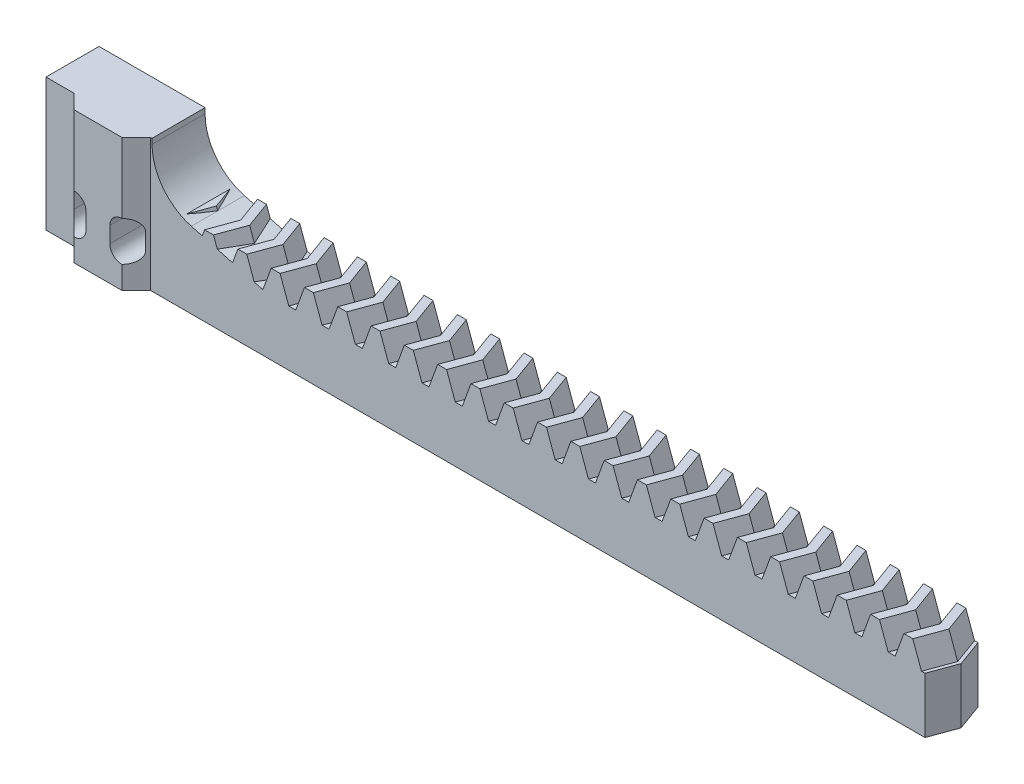
SolidWorks part; units mm, degrees
material "3D printed plastic"
ref_plane "Front Plane" through (0, 0, 0) normal (0, 0, 1) x (1, 0, 0)
ref_plane "Top Plane" through (0, 0, 0) normal (0, 1, 0) x (1, 0, 0)
ref_plane "Right Plane" through (0, 0, 0) normal (1, 0, 0) x (0, 0, -1)
sketch "Sketch1" plane through (0, 0, 0) normal (0, 0, 1) x (1, 0, 0)
  line L21 (-3.14, -10.5) -> (3.14, -10.5)
  line L22 (3.14, -10.5) -> (3.14, 0)
  line L23 (3.14, 0) -> (2.4799, 0)
  line L24 (2.4799, 0) -> (0.8421, 4.5)
  line L25 (0.8421, 4.5) -> (-0.8421, 4.5)
  line L26 (-0.8421, 4.5) -> (-2.4799, 0)
  line L27 (-2.4799, 0) -> (-3.14, 0)
  line L28 (-3.14, 0) -> (-3.14, -10.5)
  line L29 (0, -10.5) -> (0, 4.5) construction
  line L30 (-2.4799, 0) -> (2.4799, 0) construction
  line L31 (-1.57, 2.5) -> (-3.14, 2.5) construction
  line L32 (-1.57, 2.5) -> (0, 2.5) construction
  line L33 (0, 2.5) -> (1.57, 2.5) construction
  line L34 (1.57, 2.5) -> (3.14, 2.5) construction
  line L35 (3.14, 2.5) -> (3.14, 0) construction
  line L36 (-3.14, 2.5) -> (-3.14, 0) construction
  line L37 (-3.14, 0) -> (-3.126, -0.0106) construction
  dimension "D7" = 20
  dimension "D8" = 4.5
  dimension "D9" = 6.28
  dimension "D10" = 2
  dimension "D11" = 10.5
sketch "Sketch2" plane through (0, 0, 0) normal (0, 1, 0) x (1, 0, 0)
  line L0 (0, 0) -> (-1.8199, 5)
  line L1 (-2.4799, 0) -> (2.4799, 0) construction
  dimension "D1" = 70
  dimension "D2" = 5
sweep "Sweep1" add profiles "Sketch1" path "Sketch2"
mirror "Mirror2" about plane through (0, 0, 0) normal (0, 0, 1) of "Sweep1"
pattern_linear "LPattern2" count 24 spacing 6.28 along (1, 0, 0) of "Mirror2", "Sweep1"
sketch "Sketch3" plane through (0, 0, 5) normal (0, 0, 1) x (1, 0, 0)
  line L0 (0, 13.5) -> (0, 14.5)
  line L1 (0, -10.5) -> (-20, -10.5)
  line L2 (-4.9599, -10.5) -> (145.7601, -10.5) construction
  line L3 (0, -10.5) -> (0, 0) construction
  line L4 (21.7457, 0) -> (21.7457, -10.5)
  line L5 (0, 14.5) -> (-20, 14.5)
  line L6 (-20, 14.5) -> (-20, -10.5)
  line L7 (-4.9599, -10.5) -> (145.7601, -10.5) construction
  line L8 (21.7457, -10.5) -> (0, -10.5)
  line L9 (0, -10.5) -> (-0.0287, -10.5095)
  line L10 (19.5001, 0) -> (21.3199, 0) construction
  line L11 (7.4118, 3.8407) -> (21.7457, 0)
  arc A0 (0, 13.5) -> (7.4118, 3.8407) centre (10, 13.5) ccw
  dimension "D3" = 13.5
  dimension "D4" = 10
  dimension "D1" = 20
  dimension "D2" = 25
  dimension "D5" = 105
extrude "Boss-Extrude1" add sketch "Sketch3" against normal up to surface (10 mm away)
sketch "Sketch4" plane through (0, 14.5, 0) normal (0, 1, 0) x (1, 0, 0)
  line L0 (-14.7, -5) -> (-12, -7.7)
  line L2 (-12, -7.7) -> (-3, -7.7)
  line L3 (-3, -7.7) -> (-0.3, -5)
  line L4 (-0.3, -5) -> (-14.7, -5)
  line L5 (-20, 5) -> (-20, -5) construction
  line L6 (0, -5) -> (-20, -5) construction
  dimension "D1" = 5.3
  dimension "D2" = 45
  dimension "D3" = 2.7
  dimension "D4" = 14.4
extrude "Boss-Extrude2" add sketch "Sketch4" against normal up to surface (25 mm away) up to face at (79.8201, -10.5, 0)
sketch "Sketch5" plane through (0, 0, 7.7) normal (0, 0, 1) x (1, 0, 0)
  line L0 (-3, -4) -> (-3, -1) construction
  line L1 (-5.25, -4) -> (-5.25, -1)
  line L2 (-20, 14.5) -> (-20, -10.5) construction
  line L3 (-12, -2.5) -> (-3, -2.5) construction
  line L4 (-20, -10.5) -> (-14.7, -10.5) construction
  line L5 (-12, -4) -> (-12, -1) construction
  line L6 (-14.25, -4) -> (-14.25, -1)
  line L7 (-9.75, -4) -> (-9.75, -1)
  line L8 (-0.75, -4) -> (-0.75, -1)
  circle A0 centre (-12, -2.5) radius 2.25 construction
  circle A1 centre (-3, -2.5) radius 2.25 construction
  arc A2 (-14.25, -4) -> (-9.75, -4) centre (-12, -4) ccw
  arc A3 (-9.75, -1) -> (-14.25, -1) centre (-12, -1) ccw
  arc A4 (-5.25, -4) -> (-0.75, -4) centre (-3, -4) ccw
  arc A5 (-0.75, -1) -> (-5.25, -1) centre (-3, -1) ccw
  point P6 (-12, -2.5)
  point P11 (-17.35, -10.5)
  point P18 (-3, -2.5)
  dimension "D2" = 8
  dimension "D3" = 4.5
  dimension "D1" = 8
  dimension "D4" = 9
  dimension "D5" = 3
extrude "Cut-Extrude1" cut sketch "Sketch5" against normal through all
